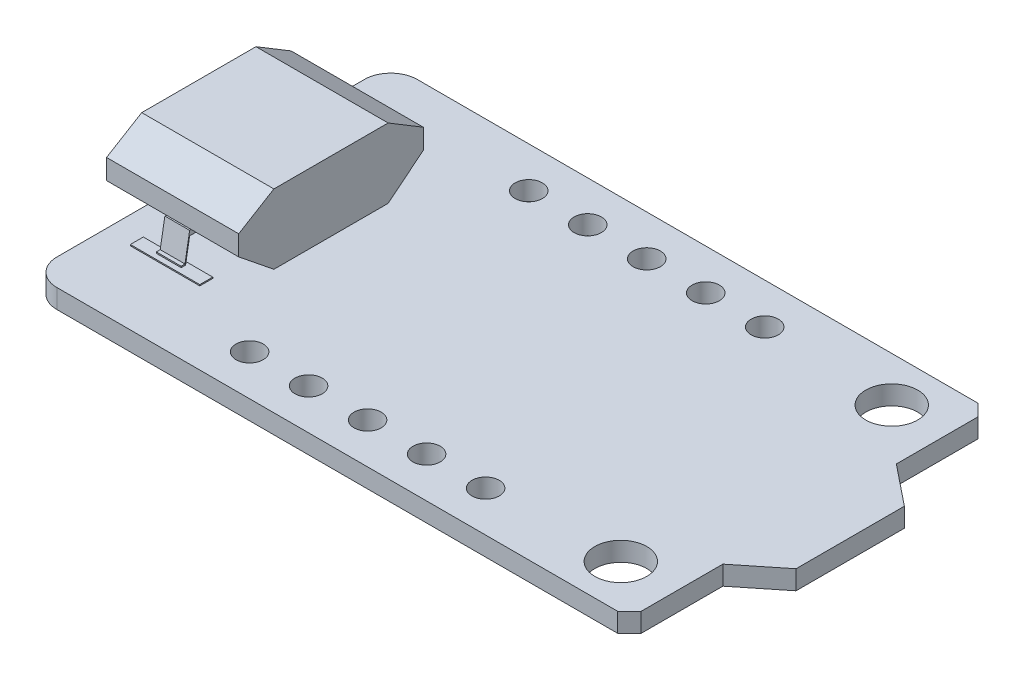
SolidWorks part; units mm, degrees
ref_plane "Front Plane" through (0, 0, 0) normal (0, 0, 1) x (1, 0, 0)
ref_plane "Top Plane" through (0, 0, 0) normal (0, 1, 0) x (1, 0, 0)
ref_plane "Right Plane" through (0, 0, 0) normal (1, 0, 0) x (0, 0, -1)
sketch "Sketch1" plane through (0, 0, 0) normal (0, 1, 0) x (1, 0, 0)
  line L0 (13.55, 7.635) -> (-13.55, -7.635) construction
  line L1 (-13.55, 7.635) -> (11.83, 7.635)
  line L2 (-13.55, 7.635) -> (-13.55, -7.635)
  line L4 (13.55, 7.635) -> (13.55, -7.635) construction
  line L5 (11.83, 28.3243) -> (11.83, -30.9439) construction
  line L6 (11.83, 3.675) -> (13.55, 2.295)
  line L7 (-13.55, 0) -> (13.55, 0) construction
  line L8 (11.83, 3.675) -> (11.83, 7.635)
  line L9 (11.83, 7.635) -> (13.55, 7.635) construction
  line L10 (-13.55, -7.635) -> (11.83, -7.635)
  line L11 (11.83, -7.635) -> (13.55, -7.635) construction
  line L12 (11.83, -3.675) -> (11.83, -7.635)
  line L13 (11.83, -3.675) -> (13.55, -2.295)
  line L14 (13.55, 2.295) -> (13.55, -2.295)
  point P7 (11.83, 3.675)
  point P8 (13.55, 2.295)
  dimension "D1" = 15.27
  dimension "D2" = 27.1
  dimension "D3" = 1.72
  dimension "D4" = 3.96
  dimension "D5" = 5.34
extrude "Boss-Extrude1" add sketch "Sketch1" along normal mid plane 0.81
fillet "Fillet1" radius 1.12 2 edges at (-13.55, 0, -7.635) (-13.55, 0, 7.635)
chamfer "Chamfer1" distance 0.5 angle 45 2 edges at (11.83, 0, 7.635) (11.83, 0, -7.635)
sketch "Sketch2" plane through (0, 0.405, 0) normal (0, 1, 0) x (1, 0, 0)
  line L0 (-13.55, 0) -> (13.55, 0) construction
  line L1 (-13.55, 6.515) -> (-13.55, -6.515) construction
  line L2 (13.55, -2.295) -> (13.55, 2.295) construction
  line L3 (9.57, 5.74) -> (9.57, 6.84) construction
  line L4 (9.57, 5.74) -> (9.57, -5.74) construction
  line L5 (9.57, -5.74) -> (9.57, -6.84) construction
  line L6 (9.57, 5.74) -> (10.67, 5.74) construction
  circle A0 centre (9.57, 5.74) radius 1.1
  circle A1 centre (9.57, -5.74) radius 1.1
  point P10 (9.57, 0)
  dimension "D1" = 2.2
  dimension "D2" = 13.68
  dimension "D3" = 2.88
extrude "Cut-Extrude1" cut sketch "Sketch2" against normal through all
sketch "Sketch3" plane through (-13.55, 0, 0) normal (-1, 0, 0) x (0, 0, 1)
  line L0 (-3.91, 1.655) -> (-2.42, 0.455)
  line L1 (-2.42, 3.405) -> (2.42, 3.405)
  line L2 (-2.42, 3.405) -> (-2.42, 0.455) construction
  line L3 (-2.42, 0.455) -> (2.42, 0.455)
  line L4 (2.42, 3.405) -> (2.42, 0.455) construction
  line L5 (-3.91, 2.505) -> (-2.42, 3.405)
  line L6 (-3.91, 2.505) -> (-3.91, 1.655)
  line L7 (0, 3.405) -> (0, 0.455) construction
  line L8 (3.91, 1.655) -> (2.42, 0.455)
  line L9 (3.91, 2.505) -> (2.42, 3.405)
  line L10 (3.91, 2.505) -> (3.91, 1.655)
  line L11 (0, 0) -> (0, 0.455) construction
  line L12 (-6.515, 0.405) -> (6.515, 0.405) construction
  point P10 (0, 1.93)
  dimension "D1" = 2.95
  dimension "D2" = 7.82
  dimension "D3" = 0.9
  dimension "D4" = 1.2
  dimension "D5" = 4.84
  dimension "D6" = 0.05
extrude "Boss-Extrude2" add sketch "Sketch3" along normal blind 0.5 and the other way blind 5.1 separate body
sketch "Sketch4" plane through (0, 0.405, 0) normal (0, 1, 0) x (1, 0, 0)
  line L0 (0, 0) -> (-16.5807, 0) construction
  line L1 (-12.4018, 4.55) -> (-9.46, 4.55)
  line L2 (-12.4018, 4.55) -> (-12.4018, 4.0002)
  line L3 (-12.4018, 4.0002) -> (-9.46, 4.0002)
  line L4 (-9.46, 4.55) -> (-9.46, 4.0002)
  line L5 (-9.46, -4.55) -> (-9.46, -4.0002)
  line L6 (-12.4018, -4.0002) -> (-9.46, -4.0002)
  line L7 (-12.4018, -4.55) -> (-12.4018, -4.0002)
  line L8 (-12.4018, -4.55) -> (-9.46, -4.55)
extrude "Boss-Extrude3" add sketch "Sketch4" along normal blind 0.05
ref_plane "Plane1" through (-11, 0, 0) normal (1, 0, 0) x (0, 0, -1)
sketch "Sketch5" plane through (-11, 0, 0) normal (1, 0, 0) x (0, 0, -1)
  line L0 (4.3254, 0.455) -> (4.3254, 0.5094)
  line L1 (4.55, 0.455) -> (4.0002, 0.455) construction
  line L2 (4.3254, 0.5094) -> (4.1621, 0.5094)
  line L3 (4.1621, 0.5094) -> (3.9644, 1.6441)
  line L4 (3.9644, 1.6441) -> (3.4984, 1.6441)
  line L5 (3.4984, 1.6441) -> (3.4984, 1.4426)
  line L6 (3.4984, 1.4426) -> (3.9644, 1.4426)
  line L7 (3.9644, 1.4426) -> (4.1365, 0.455)
  line L8 (4.1365, 0.455) -> (4.3254, 0.455)
  line L9 (0, 0) -> (0, 5.4291) construction
  line L10 (-4.1365, 0.455) -> (-4.3254, 0.455)
  line L11 (-3.9644, 1.4426) -> (-4.1365, 0.455)
  line L12 (-3.4984, 1.4426) -> (-3.9644, 1.4426)
  line L13 (-3.4984, 1.6441) -> (-3.4984, 1.4426)
  line L14 (-3.9644, 1.6441) -> (-3.4984, 1.6441)
  line L15 (-4.1621, 0.5094) -> (-3.9644, 1.6441)
  line L16 (-4.3254, 0.5094) -> (-4.1621, 0.5094)
  line L17 (-4.3254, 0.455) -> (-4.3254, 0.5094)
extrude "Boss-Extrude4" add sketch "Sketch5" along normal mid plane 1.05
sketch "Sketch6" plane through (0, 0.405, 0) normal (0, 1, 0) x (1, 0, 0)
  line L0 (13.55, 0) -> (-14.05, 0) construction
  line L1 (13.55, -2.295) -> (13.55, 2.295) construction
  line L2 (-14.05, -2.42) -> (-14.05, 2.42) construction
  line L3 (-5.9852, 5.9137) -> (-3.7107, 5.9137) construction
  circle A0 centre (-5.9852, 5.9137) radius 0.5776
  circle A1 centre (-3.4852, 5.9137) radius 0.5776
  circle A2 centre (-0.9852, 5.9137) radius 0.5776
  circle A3 centre (1.5148, 5.9137) radius 0.5776
  circle A4 centre (4.0148, 5.9137) radius 0.5776
  circle A5 centre (4.0148, -5.9137) radius 0.5776
  circle A6 centre (1.5148, -5.9137) radius 0.5776
  circle A7 centre (-0.9852, -5.9137) radius 0.5776
  circle A8 centre (-3.4852, -5.9137) radius 0.5776
  circle A9 centre (-5.9852, -5.9137) radius 0.5776
  dimension "D1" = 5
extrude "Cut-Extrude2" cut sketch "Sketch6" against normal through all
